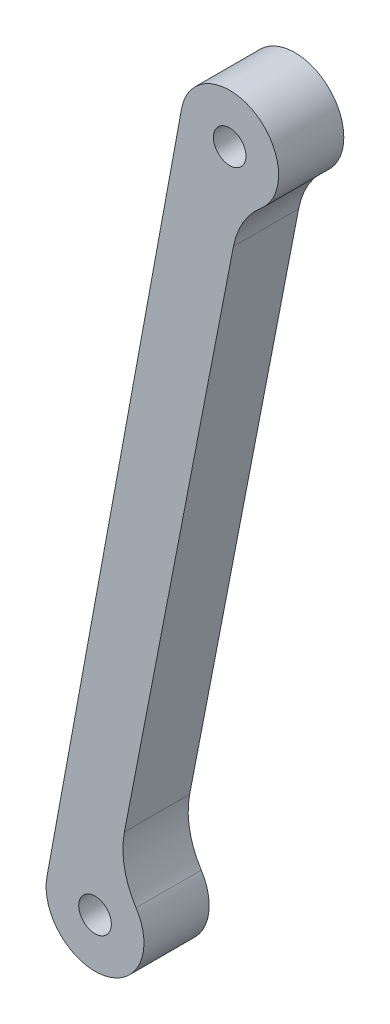
SolidWorks part; units mm, degrees
ref_plane "Спереди" through (0, 0, 0) normal (0, 0, 1) x (1, 0, 0)
ref_plane "Сверху" through (0, 0, 0) normal (0, 1, 0) x (1, 0, 0)
ref_plane "Справа" through (0, 0, 0) normal (1, 0, 0) x (0, 0, -1)
sketch "Sketch5" plane through (0, 0, 0) normal (0, 0, 1) x (1, 0, 0)
  line L0 (1.7523, 0.4742) -> (37.3029, 86.8114) construction
  line L1 (-1.0106, -0.6044) -> (29.6618, 87.5839) construction
  line L2 (0, 0) -> (17.8901, 43.1295)
  line L3 (0, 0) -> (114.3643, 0) construction
  line L4 (23.8823, 39.6684) -> (24.5035, 51.2503)
  line B0 (17.4507, 115.16) -> (29.9551, 112.6983)
  spline B1 degree 3 poles (29.9551, 112.6983) (28.321, 116.0983) (27.9284, 121.1676) (30.1713, 134.4746) (29.8473, 132.0116) (30.6222, 139.9349) (27.0176, 140.9027) knots 0 0 0 0 0.297085 0.369784 0.687298 1 1 1 1
  spline B2 degree 2 poles (27.0176, 140.9027) (20.5603, 128.6427) (17.4507, 115.16) knots 0 0 0 1 1 1
  spline B3 degree 2 poles (27.0176, 140.9027) (26.5004, 134.6878) (22.2537, 130.5645) knots 0 0 0 1 1 1
  line B4 (17.1977, 114.3508) -> (29.842, 112.2111)
  line B5 (28.7001, 84.8969) -> (10.3668, 87.513)
  spline B6 degree 1 poles (17.1977, 114.3508) (10.3668, 87.513) knots 0 0 1 1
  spline B7 degree 2 poles (29.842, 112.2111) (22.5534, 98.8452) (28.7001, 84.8969) knots 0 0 0 1 1 1
  line B8 (10.1904, 87.4159) -> (28.2572, 84.4958)
  line B9 (32.8909, 45.7292) -> (10.0695, 42.8593)
  spline B10 degree 2 poles (10.1904, 87.4159) (10.0234, 65.1379) (10.0695, 42.8593) knots 0 0 0 1 1 1
  spline B11 degree 2 poles (28.2572, 84.4958) (20.6417, 64.1094) (32.8909, 45.7292) knots 0 0 0 1 1 1
  line B12 (10.2797, 36.8758) -> (3.9253, -13.9853)
  line B13 (3.9253, -13.9853) -> (33.9594, -31.0804)
  line B14 (33.9594, -31.0804) -> (45.9193, -27.7969)
  line B15 (45.9193, -27.7969) -> (58.2918, -13.9853)
  line B16 (58.2918, -13.9853) -> (69.0331, -4.9875)
  line B17 (69.0331, -4.9875) -> (82.514, 2.0236)
  line B18 (82.514, 2.0236) -> (89.2736, 3.8794)
  line B19 (89.2736, 3.8794) -> (92.4846, 9.5208)
  line B20 (92.4846, 9.5208) -> (96.8914, 17.263)
  line B21 (96.8914, 17.263) -> (101.4978, 21.1217)
  line B22 (101.4978, 21.1217) -> (103.9241, 23.1541)
  line B23 (104.261, 27.4157) -> (104.5375, 25.5318)
  line B24 (84.192, 21.2056) -> (87.7484, 22.7822)
  line B25 (87.7484, 22.7822) -> (92.912, 27.4956)
  line B26 (71.6086, 15.6268) -> (84.192, 21.2056)
  line B27 (92.912, 27.4956) -> (95.357, 29.7274)
  line B28 (95.357, 29.7274) -> (96.8049, 29.9399)
  line B29 (71.6086, 15.6268) -> (53.4239, 15.2713)
  line B30 (48.0904, 17.5622) -> (39.9394, 26.4919)
  line B31 (39.9394, 26.4919) -> (33.9594, 37.99)
  line B32 (33.9594, 37.99) -> (10.2797, 36.8758)
  line B33 (96.8049, 29.9399) -> (99.4078, 30.2175)
  line B34 (99.4078, 30.2175) -> (102.2786, 29.261)
  line B35 (102.2786, 29.261) -> (104.261, 27.4157)
  line B36 (104.5375, 25.5318) -> (103.9241, 23.1541)
  arc B37 (53.4239, 15.2713) -> (48.0904, 17.5622) centre (53.2864, 22.3051) cw
  spline B38 degree 3 poles (104.261, 27.4157) (103.5289, 27.0494) (99.8378, 26.2685) (94.8982, 17.2338) (98.6516, 18.7375) knots 0 0 0 0 0.441207 1 1 1 1
  line B39 (27.7375, 116.5129) -> (14.1959, 87.8955)
  line B40 (27.7375, 116.5129) -> (25.9485, 114.8372)
  line B41 (25.9485, 114.8372) -> (27.5763, 114.067)
  line B42 (27.7375, 116.5129) -> (27.5763, 114.067)
  line B43 (26.1527, 88.0864) -> (17.8901, 43.1295)
  line B44 (19.3622, 85.005) -> (23.8823, 39.6684)
  line B45 (19.3622, 85.005) -> (17.7584, 73.9508)
  line B46 (17.7584, 73.9508) -> (23.117, 74.485)
  line B47 (23.117, 74.485) -> (19.3622, 85.005)
  line B48 (26.1527, 88.0864) -> (23.7481, 82.7635)
  line B49 (23.7481, 82.7635) -> (25.1278, 82.5099)
  line B50 (25.1278, 82.5099) -> (26.5087, 82.2561)
  line B51 (26.5087, 82.2561) -> (26.1527, 88.0864)
  line B52 (26.1527, 88.0864) -> (19.3622, 85.005)
  line B53 (19.3622, 85.005) -> (22.3683, 87.7853)
  line B54 (22.3683, 87.7853) -> (22.9012, 86.6109)
  line B55 (22.9012, 86.6109) -> (23.4998, 85.2917)
  line B56 (23.4998, 85.2917) -> (19.3622, 85.005)
  dimension "D1" = 93.37
  dimension "D2" = 93.37
  dimension "D4" = 67.471
  dimension "D5" = 8.764
sketch_block_instance "Block1-1"
sketch_block "Block1"
sketch_block_instance "Block2-1"
sketch_block "Block2"
sketch_block_instance "Block3-1"
sketch_block "Block3"
sketch_block_instance "Block18-1"
sketch_block "Block18"
sketch_block_instance "Block44-1"
sketch_block "Block44"
sketch_block_instance "Block46-1"
sketch_block "Block46"
sketch_block_instance "Block47-1"
sketch_block "Block47"
sketch_block_instance "Block48-1"
sketch_block "Block48"
sketch_block_instance "Block50-1"
sketch_block "Block50"
sketch "Sketch7" plane through (0, 0, 0) normal (0, 0, 1) x (1, 0, 0)
  line L0 (14.9395, 43.6718) -> (23.1953, 88.5924)
  line L1 (19.6932, 48.436) -> (26.3767, 82.8719)
  arc A0 (14.9395, 43.6718) -> (20.4069, 44.7622) centre (17.8901, 43.1295) ccw
  arc A1 (28.0731, 85.7511) -> (23.1953, 88.5924) centre (26.1459, 88.0502) ccw
  circle A2 centre (17.8901, 43.1295) radius 1
  circle A3 centre (26.1459, 88.0502) radius 1
  arc A4 (26.3767, 82.8719) -> (28.0731, 85.7511) centre (31.2851, 81.9192) cw
  arc A5 (19.6932, 48.436) -> (20.4069, 44.7622) centre (24.6016, 47.4833) ccw
  dimension "D1" = 2
  dimension "D2" = 6
  dimension "D3" = 5
extrude "Boss-Extrude2" add sketch "Sketch7" along normal blind 4
sketch "Sketch8" plane through (0, 0, 4) normal (0, 0, 1) x (1, 0, 0)
  line L0 (26.1459, 91.0502) -> (26.1459, 89.0502)
  line L1 (26.1459, 87.0502) -> (26.1459, 85.0502)
  arc A0 (26.1459, 85.0502) -> (26.1459, 91.0502) centre (26.1459, 88.0502) ccw
  arc A1 (26.1459, 87.0502) -> (26.1459, 89.0502) centre (26.1459, 88.0502) ccw
